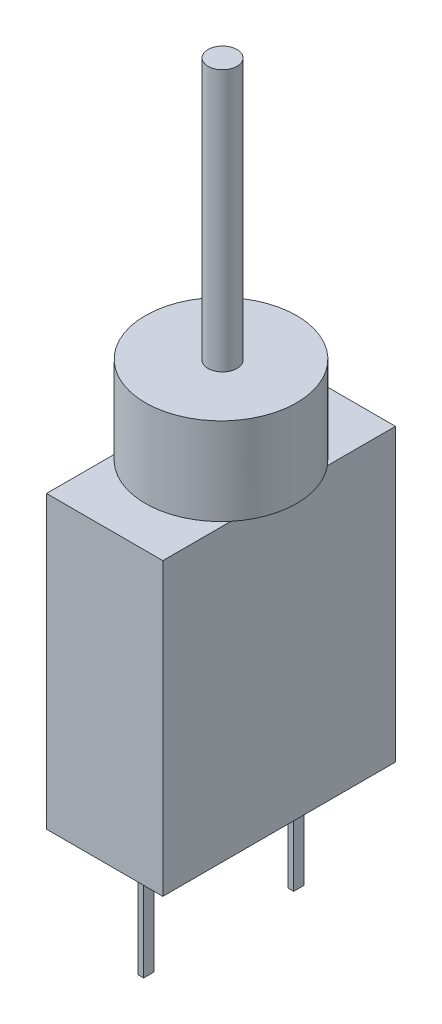
SolidWorks part; units mm, degrees
ref_plane "Plan de face" through (0, 0, 0) normal (0, 0, 1) x (1, 0, 0)
ref_plane "Plan de dessus" through (0, 0, 0) normal (0, 1, 0) x (1, 0, 0)
ref_plane "Plan de droite" through (0, 0, 0) normal (1, 0, 0) x (0, 0, -1)
sketch "Esquisse1" plane through (0, 0, 0) normal (1, 0, 0) x (0, 0, -1)
  line L1 (-4, 5) -> (4, 5)
  line L2 (-4, 5) -> (-4, -5)
  line L3 (-4, -5) -> (4, -5)
  line L4 (4, 5) -> (4, -5)
  line L5 (-4, 5) -> (4, -5) construction
  line L6 (-4, -5) -> (4, 5) construction
  point P0 (0, 0)
  dimension "D1" = 10
  dimension "D2" = 8
extrude "Boss.-Extru.1" add sketch "Esquisse1" along normal blind 4
sketch "Esquisse2" plane through (0, -5, 0) normal (0, -1, 0) x (1, 0, 0)
  line L0 (2, 4) -> (2, -4) construction
  line L1 (4, 4) -> (0, 4) construction
  line L2 (4, -4) -> (0, -4) construction
  line L4 (1.8994, 2.7607) -> (2.1006, 2.7607)
  line L5 (1.8994, 2.7607) -> (1.8994, 2.4008)
  line L6 (1.8994, 2.4008) -> (2.1006, 2.4008)
  line L7 (2.1006, 2.7607) -> (2.1006, 2.4008)
  line L8 (1.8994, 2.7607) -> (2.1006, 2.4008) construction
  line L9 (1.8994, 2.4008) -> (2.1006, 2.7607) construction
  point P6 (2, 2.5807)
extrude "Boss.-Extru.2" add sketch "Esquisse2" along normal blind 4
mirror "Symétrie1" about plane through (0, 0, 0) normal (0, 0, 1) of "Boss.-Extru.2"
sketch "Esquisse3" plane through (0, 5, 0) normal (0, 1, 0) x (1, 0, 0)
  line L0 (2, 4) -> (2, -4) construction
  line L1 (4, 4) -> (0, 4) construction
  line L2 (4, -4) -> (0, -4) construction
  circle A0 centre (2, 0) radius 2.6
  dimension "D1" = 5.2
extrude "Boss.-Extru.3" add sketch "Esquisse3" along normal blind 3
sketch "Esquisse4" plane through (0, 8, 0) normal (0, 1, 0) x (1, 0, 0)
  circle A0 centre (2.0535, 0) radius 0.5
  dimension "D1" = 1
extrude "Boss.-Extru.4" add sketch "Esquisse4" along normal blind 9
